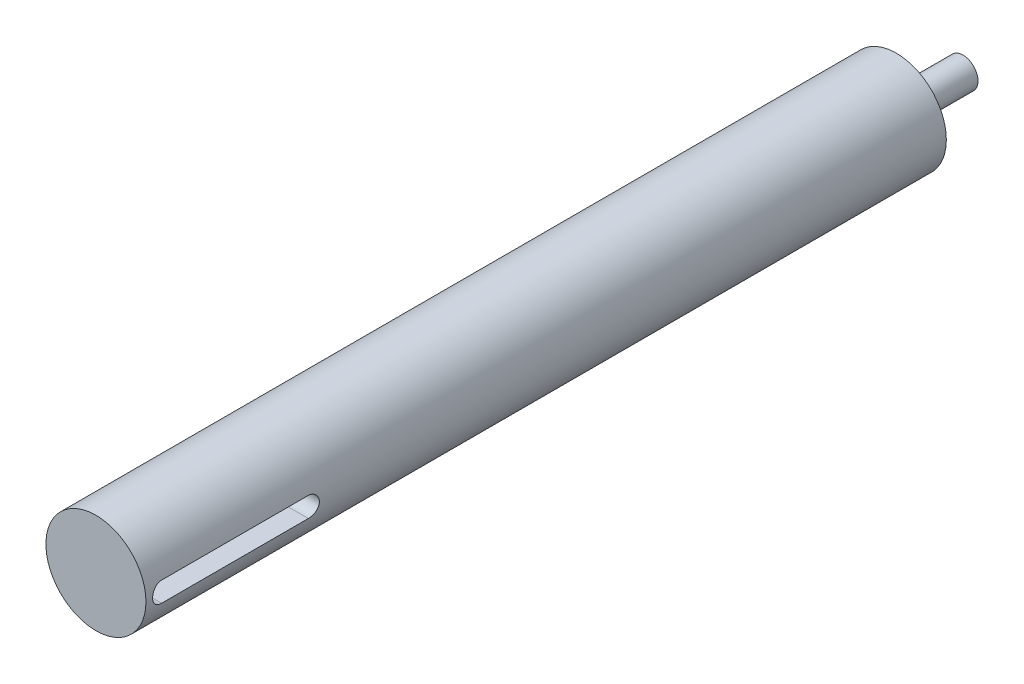
SolidWorks part; units mm, degrees
ref_plane "前视基准面" through (0, 0, 0) normal (0, 0, 1) x (1, 0, 0)
ref_plane "上视基准面" through (0, 0, 0) normal (0, 1, 0) x (1, 0, 0)
ref_plane "右视基准面" through (0, 0, 0) normal (1, 0, 0) x (0, 0, -1)
sketch "草图1" plane through (0, 0, 0) normal (0, 0, 1) x (1, 0, 0)
  circle A0 centre (0, 0) radius 15
  dimension "D1" = 30
extrude "凸台-拉伸1" add sketch "草图1" along normal blind 240
sketch "草图4" plane through (0, 0, 0) normal (0, 0, -1) x (-1, 0, 0)
  circle A0 centre (0, 0) radius 4.5
  dimension "D1" = 9
extrude "凸台-拉伸2" add sketch "草图4" along normal blind 20
ref_plane "基准面1" through (15, 0, 0) normal (1, 0, 0) x (0, 0, -1)
sketch "草图5" plane through (15, 0, 0) normal (1, 0, 0) x (0, 0, -1)
  line L0 (-235, 0) -> (-191, 0) construction
  line L4 (-235, 3) -> (-191, 3)
  line L5 (-235, -3) -> (-191, -3)
  line L7 (-240, 15) -> (-240, -15) construction
  arc A2 (-235, 3) -> (-235, -3) centre (-235, 0) ccw
  arc A3 (-191, -3) -> (-191, 3) centre (-191, 0) ccw
  point P2 (-213, 0)
  dimension "D1" = 3
  dimension "D2" = 44
  dimension "D3" = 5
extrude "切除-拉伸3" cut sketch "草图5" against normal blind 8
